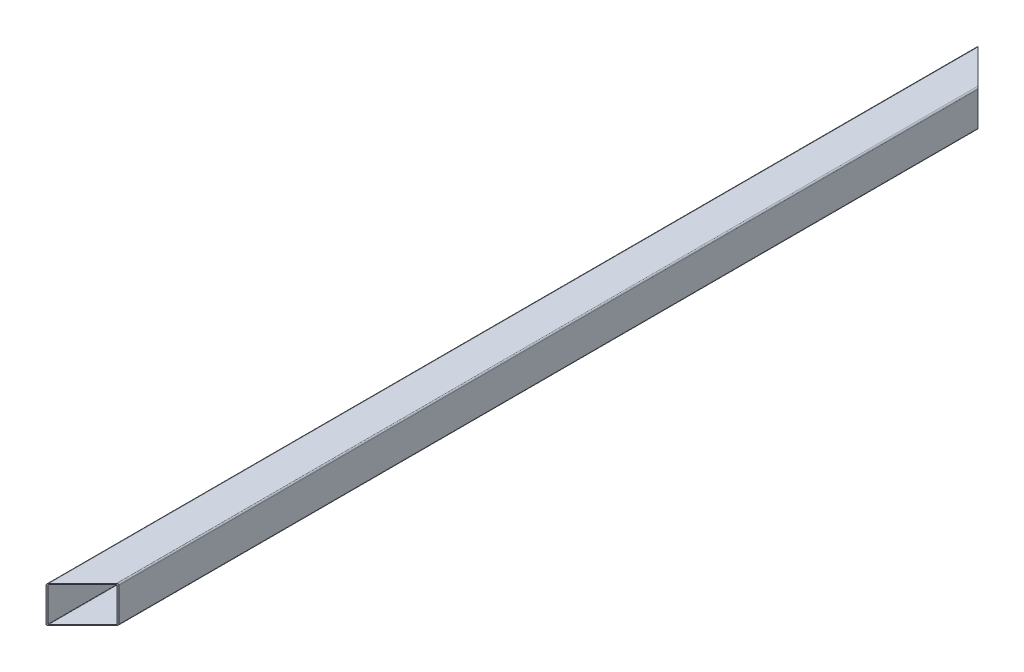
SolidWorks part; units mm, degrees
material "AISI 1020 Steel, Cold Rolled"
ref_plane "Front Plane" through (0, 0, 0) normal (0, 0, 1) x (1, 0, 0)
ref_plane "Top Plane" through (0, 0, 0) normal (0, 1, 0) x (1, 0, 0)
ref_plane "Right Plane" through (0, 0, 0) normal (1, 0, 0) x (0, 0, -1)
sketch "Sketch1" plane through (0, 0, 0) normal (0, 1, 0) x (1, 0, 0)
  line L0 (0, 0) -> (0, 1020)
  dimension "D1" = 1020
other "Structural Member1"
ref_plane "Plane1" through (0, 0, 0) normal (0, 0, -1) x (-1, 0, 0)
sketch "Sketch12" plane through (0, 0, 0) normal (0, 0, -1) x (-1, 0, 0)
  line L0 (-18.5, -18.8) -> (18.5, -18.8)
  line L1 (-18.8, -18.5) -> (-18.8, 18.5)
  line L2 (18.5, 18.8) -> (-18.5, 18.8)
  line L3 (18.8, 18.5) -> (18.8, -18.5)
  line L4 (-18.5, -20) -> (18.5, -20)
  line L5 (-20, -18.5) -> (-20, 18.5)
  line L6 (18.5, 20) -> (-18.5, 20)
  line L7 (20, 18.5) -> (20, -18.5)
  arc A0 (20, 18.5) -> (18.5, 20) centre (18.5, 18.5) ccw
  arc A1 (18.5, -20) -> (20, -18.5) centre (18.5, -18.5) ccw
  arc A2 (-20, -18.5) -> (-18.5, -20) centre (-18.5, -18.5) ccw
  arc A3 (-18.5, 20) -> (-20, 18.5) centre (-18.5, 18.5) ccw
  arc A4 (-18.5, 18.8) -> (-18.8, 18.5) centre (-18.5, 18.5) ccw
  arc A5 (18.8, 18.5) -> (18.5, 18.8) centre (18.5, 18.5) ccw
  arc A6 (18.5, -18.8) -> (18.8, -18.5) centre (18.5, -18.5) ccw
  arc A7 (-18.8, -18.5) -> (-18.5, -18.8) centre (-18.5, -18.5) ccw
  point P0 (-20, 0)
  point P1 (20, 0)
  point P2 (0, 20)
  point P3 (0, -20)
  point P4 (0, 0)
  point P5 (-20, -20)
  point P6 (20, -20)
  point P7 (20, 20)
  point P8 (-20, 20)
  point P33 (0, 0)
  dimension "D1" = 1.5
  dimension "Thickness" = 1.2
  dimension "V_leg" = 40
ref_plane "Plane2" through (0, 50, 0) normal (0, 1, 0) x (1, 0, 0)
sketch "Sketch18" plane through (0, 50, 0) normal (0, 1, 0) x (1, 0, 0)
  line L0 (-20, 1020) -> (31.2451, 968.7549)
  line L1 (31.2451, 968.7549) -> (31.2451, 1020)
  line L2 (31.2451, 1020) -> (-20, 1020)
  line L3 (-20, 0) -> (27.8459, 47.8459)
  line L4 (27.8459, 47.8459) -> (27.8459, 0)
  line L5 (27.8459, 0) -> (-20, 0)
extrude "Cut-Extrude4" cut sketch "Sketch18" against normal blind 120
